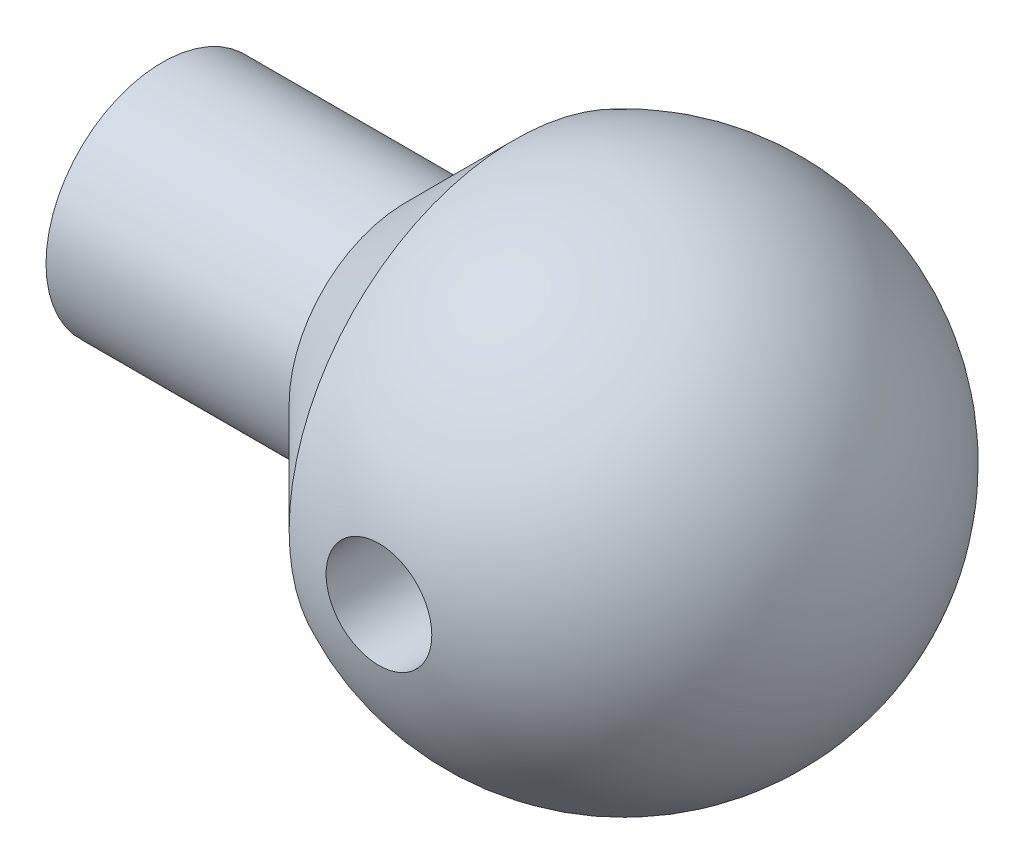
SolidWorks part; units mm, degrees
ref_plane "前视基准面" through (0, 0, 0) normal (0, 0, 1) x (1, 0, 0)
ref_plane "上视基准面" through (0, 0, 0) normal (0, 1, 0) x (1, 0, 0)
ref_plane "右视基准面" through (0, 0, 0) normal (1, 0, 0) x (0, 0, -1)
sketch "草图1" plane through (0, 0, 0) normal (0, 0, 1) x (1, 0, 0)
  line L0 (0, 0) -> (1.9828, -3.3)
  line L1 (1.9828, -3.3) -> (8.8828, -3.3)
  line L2 (0, 0) -> (20.6459, 0) construction
  line L3 (8.8828, -3.3) -> (11.9828, -6.4)
  line L5 (0, 0) -> (22.1941, 0)
  arc A0 (11.9828, -6.4) -> (22.1941, 0) centre (15.0828, 0) ccw
  dimension "D6" = 3.1
  dimension "D5" = 10
  dimension "D4" = 6.4
  dimension "D1" = 59
  dimension "D2" = 3.3
  dimension "D3" = 45
revolve "旋转1" add sketch "草图1" angle 360 about L2
sketch "草图8" plane through (0, 0, 0) normal (0, 0, 1) x (1, 0, 0)
  circle A0 centre (15.0828, 0) radius 1.5
  dimension "2" = 3
extrude "切除-拉伸1" cut sketch "草图8" against normal through all both and the other way through all
